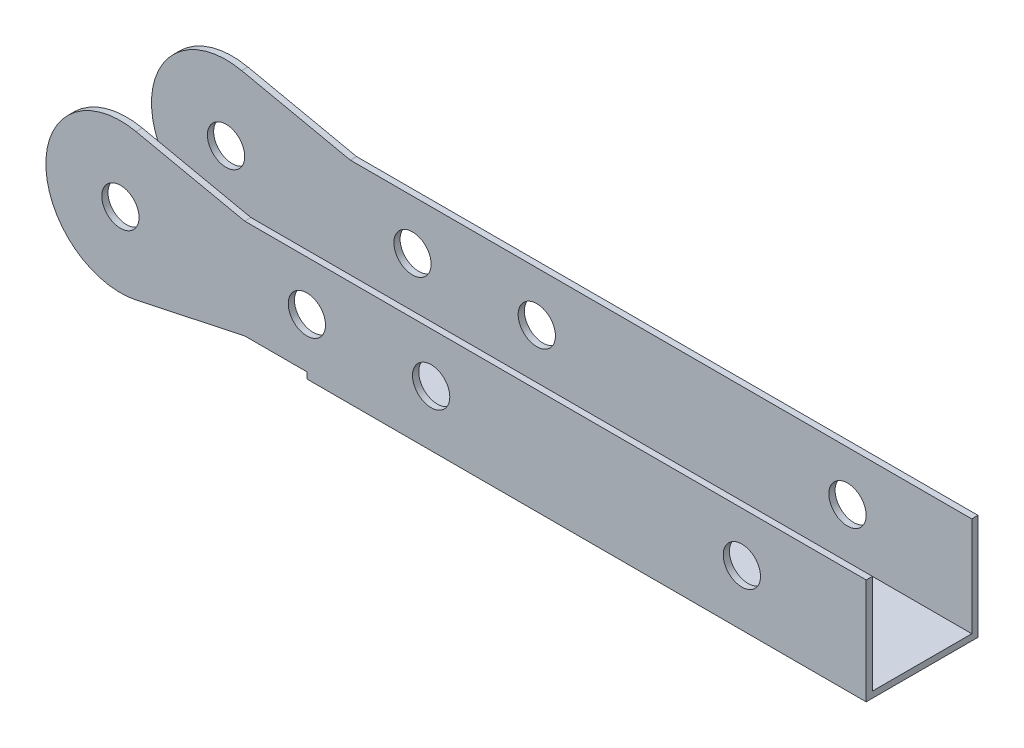
SolidWorks part; units mm, degrees
ref_plane "前视基准面" through (0, 0, 0) normal (0, 0, 1) x (1, 0, 0)
ref_plane "上视基准面" through (0, 0, 0) normal (0, 1, 0) x (1, 0, 0)
ref_plane "右视基准面" through (0, 0, 0) normal (1, 0, 0) x (0, 0, -1)
sketch "草图1" plane through (0, 0, 0) normal (0, 0, 1) x (1, 0, 0)
  line L0 (23.2, 8.0104) -> (-26.8, 8.0104)
  line L1 (-26.8, 0.0104) -> (23.2, 0.0104)
  line L2 (-60.7008, 4.0104) -> (100.6682, 4.0104) construction
  line L3 (23.2, 8.0104) -> (23.2, 0.0104)
  line L6 (-26.8, 8.0104) -> (-35.5471, 9.8781)
  line L7 (-26.8, 0.0104) -> (-35.5471, -1.8573)
  circle A0 centre (-36.8, 4.0104) radius 1.5
  arc A1 (-35.5471, 9.8781) -> (-35.5471, -1.8573) centre (-36.8, 4.0104) ccw
  circle A2 centre (-21.8, 4.0104) radius 1.5
  circle A3 centre (-11.8, 4.0104) radius 1.5
  circle A4 centre (13.2, 4.0104) radius 1.5
  dimension "D1" = 4
  dimension "D4" = 15
  dimension "D5" = 3
  dimension "D6" = 12
  dimension "D2" = 3
  dimension "D3" = 25
  dimension "D7" = 3
  dimension "D8" = 10
  dimension "D9" = 10
  dimension "D10" = 50
  dimension "D11" = 4
  dimension "D12" = 50
ref_plane "基准面1" through (0, 0.0104, 0) normal (0, -1, 0) x (1, 0, 0)
ref_plane "基准面2" through (0, 0, 8) normal (0, 0, 1) x (1, 0, 0)
sketch "草图3" plane through (0, 0, 8) normal (0, 0, 1) x (1, 0, 0)
  line L5 (-26.8, 8.0104) -> (-35.5471, 9.8781)
  line L6 (23.2, 8.0104) -> (-26.8, 8.0104)
  line L7 (23.2, 0.0104) -> (23.2, 8.0104)
  line L8 (-26.8, 0.0104) -> (23.2, 0.0104)
  line L9 (-35.5471, -1.8573) -> (-26.8, 0.0104)
  line L10 (-26.8, 8.0104) -> (-35.5471, 9.8781)
  line L11 (23.2, 8.0104) -> (-26.8, 8.0104)
  line L12 (23.2, 0.0104) -> (23.2, 8.0104)
  line L13 (-26.8, 0.0104) -> (23.2, 0.0104)
  line L14 (-35.5471, -1.8573) -> (-26.8, 0.0104)
  circle A1 centre (13.2, 4.0104) radius 1.5
  circle A2 centre (13.2, 4.0104) radius 1.5
  circle A3 centre (-11.8, 4.0104) radius 1.5
  circle A4 centre (-11.8, 4.0104) radius 1.5
  circle A5 centre (-21.8, 4.0104) radius 1.5
  circle A6 centre (-21.8, 4.0104) radius 1.5
  circle A7 centre (-36.8, 4.0104) radius 1.5
  circle A8 centre (-36.8, 4.0104) radius 1.5
  arc A9 (-35.5471, 9.8781) -> (-35.5471, -1.8573) centre (-36.8, 4.0104) ccw
  arc A10 (-35.5471, 9.8781) -> (-35.5471, -1.8573) centre (-36.8, 4.0104) ccw
  dimension "D1" = 0
  dimension "D2" = 0
  dimension "D3" = 0
  dimension "D4" = 0
  dimension "D5" = 0
extrude "凸台-拉伸1" add sketch "草图3" along normal blind 0.5
extrude "凸台-拉伸2" add sketch "草图1" against normal blind 0.5 separate body
sketch "草图4" plane through (0, 0.0104, 0) normal (0, -1, 0) x (1, 0, 0)
  line L0 (23.2, 8.5) -> (23.2, -0.5)
  line L1 (23.2, -0.5) -> (-21.8, -0.5)
  line L2 (-26.8, -0.5) -> (23.2, -0.5) construction
  line L3 (-21.8, -0.5) -> (-21.8, 8.5)
  line L4 (-26.8, 8.5) -> (23.2, 8.5) construction
  line L5 (-21.8, 8.5) -> (23.2, 8.5)
  line L6 (-36.8, 6.7279) -> (-36.8, -2.3916) construction
  line L7 (-36.8, 8.5) -> (-36.8, 8) construction
  dimension "D1" = 15
extrude "凸台-拉伸3" add sketch "草图4" along normal blind 0.5
